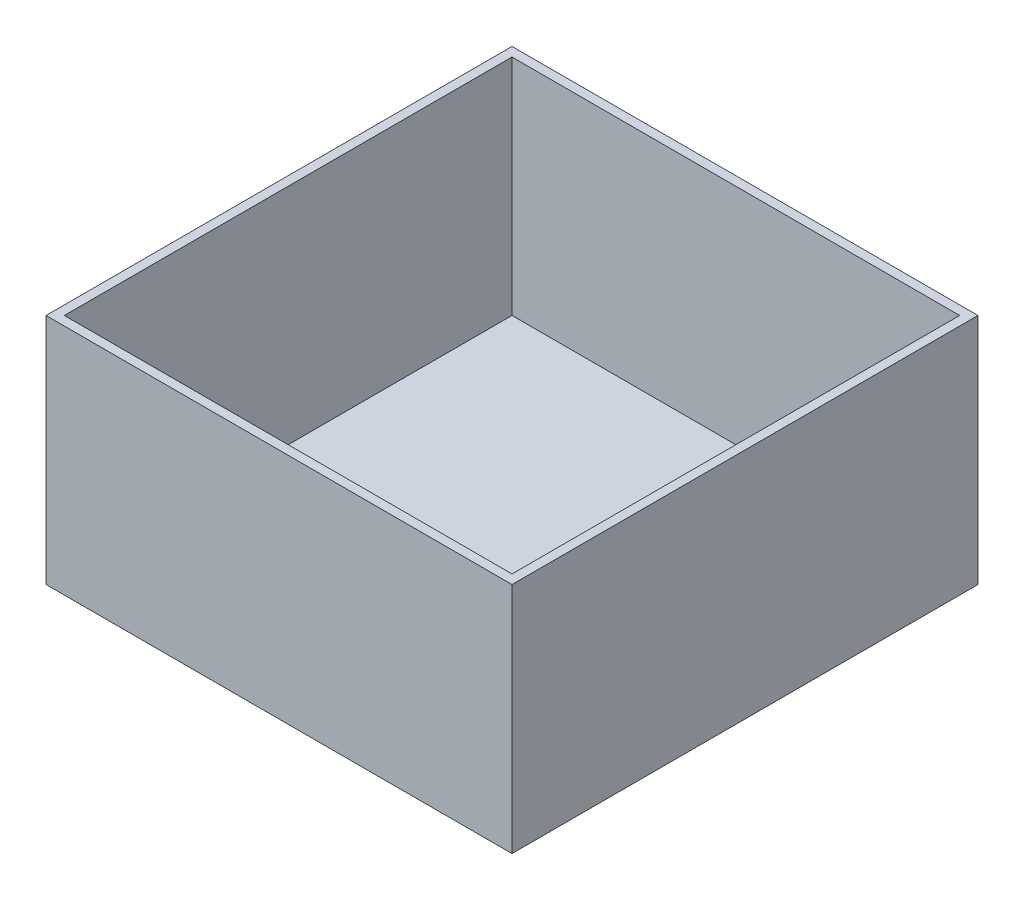
SolidWorks part; units mm, degrees
ref_plane "Front Plane" through (0, 0, 0) normal (0, 0, 1) x (1, 0, 0)
ref_plane "Top Plane" through (0, 0, 0) normal (0, 1, 0) x (1, 0, 0)
ref_plane "Right Plane" through (0, 0, 0) normal (1, 0, 0) x (0, 0, -1)
sketch "Sketch1" plane through (0, 0, 0) normal (0, 1, 0) x (1, 0, 0)
  line L1 (50.8, -50.8) -> (-50.8, -50.8)
  line L2 (50.8, -50.8) -> (50.8, 50.8)
  line L3 (50.8, 50.8) -> (-50.8, 50.8)
  line L4 (-50.8, -50.8) -> (-50.8, 50.8)
  line L5 (50.8, -50.8) -> (-50.8, 50.8) construction
  line L6 (50.8, 50.8) -> (-50.8, -50.8) construction
  point P0 (0, 0)
  dimension "D1" = 101.6
  dimension "D2" = 101.6
extrude "Boss-Extrude1" add sketch "Sketch1" along normal blind 50.8
shell "Shell1" thickness 2
equation "\"D1@Boss-Extrude1\"=2in"
equation "\"D2@Sketch1\"=4in"
equation "\"D1@Sketch1\"=4in"
